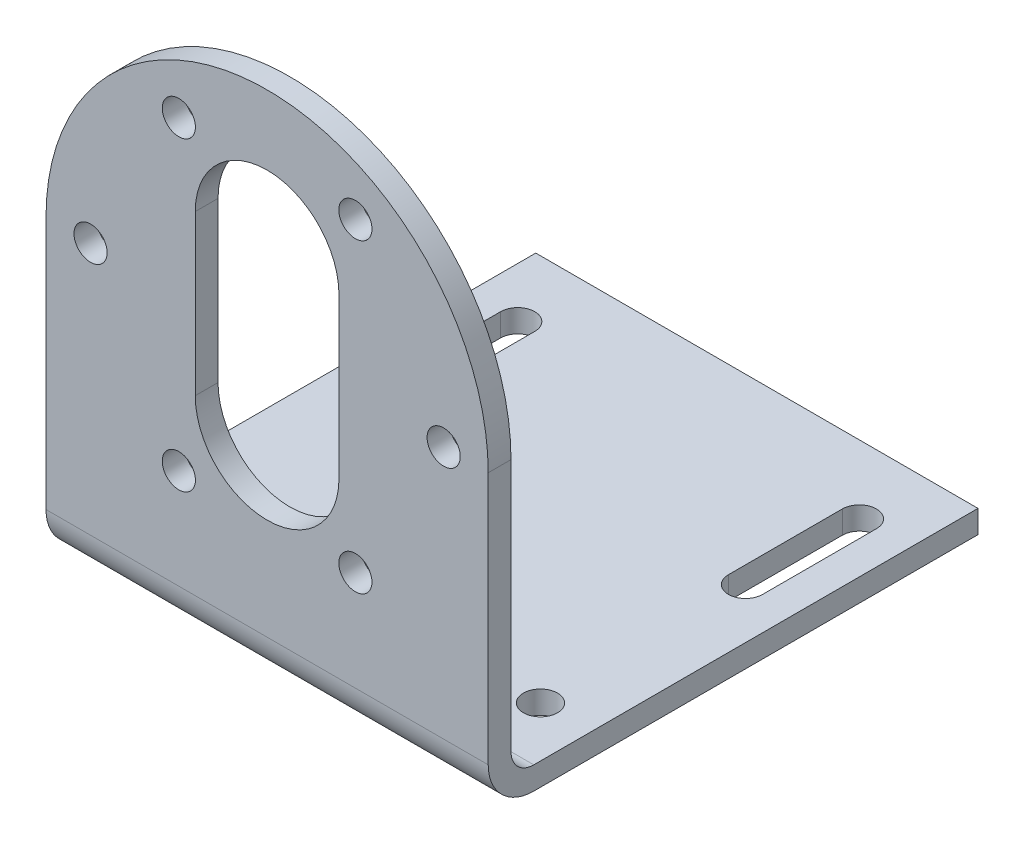
SolidWorks part; units mm, degrees
ref_plane "前视基准面" through (0, 0, 0) normal (0, 0, 1) x (1, 0, 0)
ref_plane "上视基准面" through (0, 0, 0) normal (0, 1, 0) x (1, 0, 0)
ref_plane "右视基准面" through (0, 0, 0) normal (1, 0, 0) x (0, 0, -1)
sketch "草图2" plane through (0, 0, 0) normal (0, 0, 1) x (1, 0, 0)
  line L2 (-19.4126, 26.207) -> (-19.4126, 0)
  line L3 (-19.4126, 0) -> (19.4126, 0)
  line L4 (19.4126, 26.207) -> (19.4126, 0)
  line L5 (-6.3091, 33.207) -> (-6.3091, 19.207)
  line L7 (6.3091, 33.207) -> (6.3091, 19.207)
  arc A0 (19.4126, 26.207) -> (-19.4126, 26.207) centre (0, 26.207) ccw
  circle A1 centre (0, 26.207) radius 15.5 construction
  circle A2 centre (15.5, 26.207) radius 1.4559
  circle A3 centre (7.75, 12.7836) radius 1.4559
  circle A4 centre (-7.75, 12.7836) radius 1.4559
  circle A5 centre (-15.5, 26.207) radius 1.4559
  circle A6 centre (-7.75, 39.6304) radius 1.4559
  circle A7 centre (7.75, 39.6304) radius 1.4559
  arc A8 (6.3091, 33.207) -> (-6.3091, 33.207) centre (0, 33.207) ccw
  arc A9 (-6.3091, 19.207) -> (6.3091, 19.207) centre (0, 19.207) ccw
  point P21 (0, 26.207)
  dimension "D1" = 6
  dimension "D2" = 14
  dimension "D3" = 7
extrude "凸台-拉伸1" add sketch "草图2" along normal blind 2
sketch "草图3" plane through (0, 0, 2) normal (0, 0, 1) x (1, 0, 0)
  line L0 (19.4126, 0) -> (19.4126, 26.207) construction
  line L1 (-19.4126, 0) -> (19.4126, 0)
  line L2 (-19.4126, 0) -> (-19.4126, 2)
  line L3 (-19.4126, 2) -> (19.4126, 2)
  line L4 (19.4126, 0) -> (19.4126, 2)
extrude "凸台-拉伸2" add sketch "草图3" against normal blind 43
sketch "草图4" plane through (0, 2, 0) normal (0, 1, 0) x (1, 0, 0)
  line L0 (-15, 13.2612) -> (-15, 37.8064) construction
  line L1 (15, 13.2612) -> (15, 36.4005) construction
  line L2 (-16.5, 35) -> (-16.5, 25)
  line L3 (-13.5, 35) -> (-13.5, 25)
  line L4 (13.5, 35) -> (13.5, 25)
  line L5 (16.5, 35) -> (16.5, 25)
  circle A0 centre (-15, 7) radius 1.5
  circle A1 centre (15, 7) radius 1.5
  arc A2 (-13.5, 35) -> (-16.5, 35) centre (-15, 35) ccw
  arc A3 (16.5, 35) -> (13.5, 35) centre (15, 35) ccw
  arc A4 (13.5, 25) -> (16.5, 25) centre (15, 25) ccw
  arc A5 (-16.5, 25) -> (-13.5, 25) centre (-15, 25) ccw
extrude "切除-拉伸1" cut sketch "草图4" against normal blind 10
fillet "圆角1" radius 4 1 edges at (0, 0, 2)
fillet "圆角2" radius 2 1 edges at (0, 2, 0)
